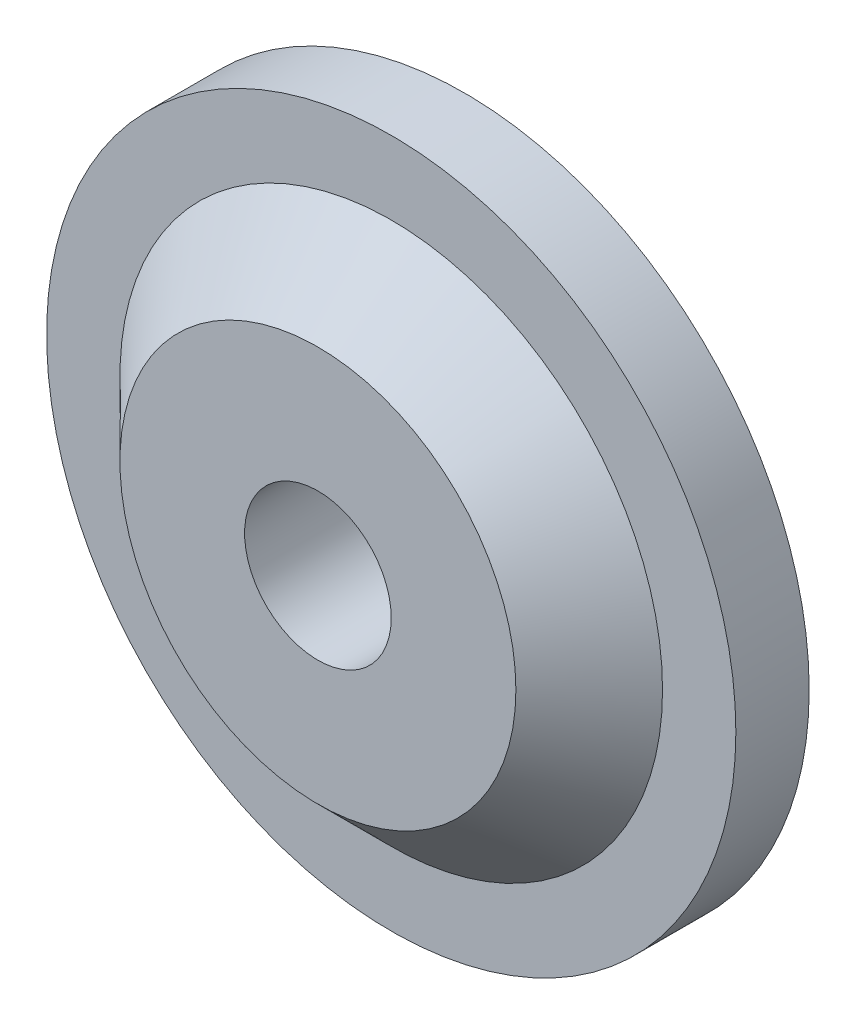
SolidWorks part; units mm, degrees
material "6061-T6 (SS)"
ref_plane "Front Plane" through (0, 0, 0) normal (0, 0, 1) x (1, 0, 0)
ref_plane "Top Plane" through (0, 0, 0) normal (0, 1, 0) x (1, 0, 0)
ref_plane "Right Plane" through (0, 0, 0) normal (1, 0, 0) x (0, 0, -1)
sketch "Sketch1" plane through (0, 0, 0) normal (0, 0, 1) x (1, 0, 0)
  circle A0 centre (0, 0) radius 14.9225
  circle A1 centre (0, 0) radius 3.175
  dimension "D1" = 29.845
  dimension "D2" = 6.35
extrude "Boss-Extrude1" add sketch "Sketch1" along normal blind 6.35
sketch "Sketch2" plane through (0, 0, 0) normal (1, 0, 0) x (0, 0, -1)
  line L0 (-6.35, 14.9225) -> (-6.35, -14.9225) construction
  line L1 (-6.35, 14.9225) -> (-3.175, 14.9225)
  line L2 (-6.35, 14.9225) -> (-6.35, 8.5725)
  line L3 (-6.35, 8.5725) -> (-3.175, 11.7475)
  line L4 (-3.175, 14.9225) -> (-3.175, 11.7475)
  line L5 (0, 14.9225) -> (-6.35, 14.9225) construction
  dimension "D1" = 3.175
  dimension "D2" = 11.7475
  dimension "D3" = 135
revolve "Cut-Revolve1" cut sketch "Sketch2" angle 360 about axis through (0, 0, 6.35) along (0, 0, -1)
